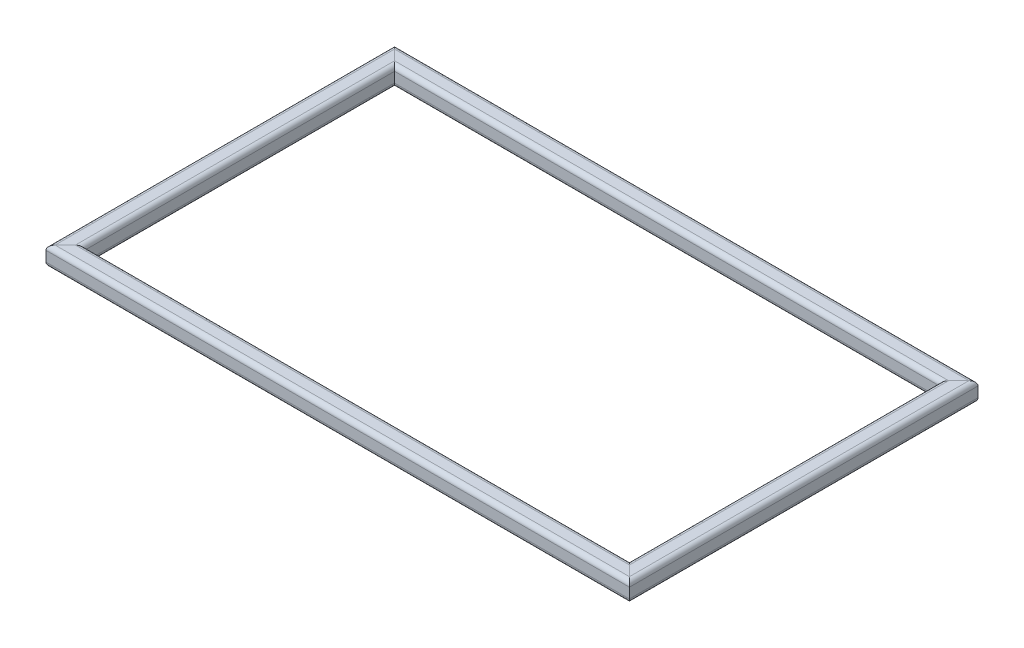
SolidWorks part; units mm, degrees
ref_plane "Alzado" through (0, 0, 0) normal (0, 0, 1) x (1, 0, 0)
ref_plane "Planta" through (0, 0, 0) normal (0, 1, 0) x (1, 0, 0)
ref_plane "Vista lateral" through (0, 0, 0) normal (1, 0, 0) x (0, 0, -1)
sketch "Croquis1" plane through (0, 0, 0) normal (0, 1, 0) x (1, 0, 0)
  line L1 (-385, 230) -> (385, 230)
  line L2 (-385, 230) -> (-385, -230)
  line L3 (-385, -230) -> (385, -230)
  line L4 (385, 230) -> (385, -230)
  line L5 (-385, 230) -> (385, -230) construction
  line L6 (-385, -230) -> (385, 230) construction
  point P0 (0, 0)
  dimension "D1" = 770
  dimension "D2" = 460
other "Tubo cuadrado 2 X 2 X 0.25(1)"
ref_plane "Plano1" through (-372.3, 12.7, -230) normal (0, 0, 1) x (1, 0, 0)
sketch "Sketch1" plane through (-372.3, 12.7, -230) normal (0, 0, 1) x (1, 0, 0)
  line L0 (-6.7, -9.7) -> (6.7, -9.7)
  line L1 (-9.7, -6.7) -> (-9.7, 6.7)
  line L2 (6.7, 9.7) -> (-6.7, 9.7)
  line L3 (9.7, 6.7) -> (9.7, -6.7)
  line L4 (-6.7, -12.7) -> (6.7, -12.7)
  line L5 (-12.7, -6.7) -> (-12.7, 6.7)
  line L6 (6.7, 12.7) -> (-6.7, 12.7)
  line L7 (12.7, 6.7) -> (12.7, -6.7)
  line L8 (0, 0) -> (9.7, 0) construction
  line L9 (0, 0) -> (0, 9.7) construction
  arc A0 (12.7, 6.7) -> (6.7, 12.7) centre (6.7, 6.7) ccw
  arc A1 (6.7, -12.7) -> (12.7, -6.7) centre (6.7, -6.7) ccw
  arc A2 (-12.7, -6.7) -> (-6.7, -12.7) centre (-6.7, -6.7) ccw
  arc A3 (-6.7, 12.7) -> (-12.7, 6.7) centre (-6.7, 6.7) ccw
  arc A4 (-6.7, 9.7) -> (-9.7, 6.7) centre (-6.7, 6.7) ccw
  arc A5 (9.7, 6.7) -> (6.7, 9.7) centre (6.7, 6.7) ccw
  arc A6 (6.7, -9.7) -> (9.7, -6.7) centre (6.7, -6.7) ccw
  arc A7 (-9.7, -6.7) -> (-6.7, -9.7) centre (-6.7, -6.7) ccw
  point P3 (0, 12.7)
  point P4 (12.7, 0)
  point P5 (0, -12.7)
  point P6 (-12.7, 0)
  point P7 (-12.7, 12.7)
  point P8 (-12.7, -12.7)
  point P33 (0, 0)
  point P35 (12.7, -12.7)
  point P36 (12.7, 12.7)
  point P37 (0, 0)
  dimension "D1" = 6
  dimension "Thickness" = 3
  dimension "V_leg" = 25.4
